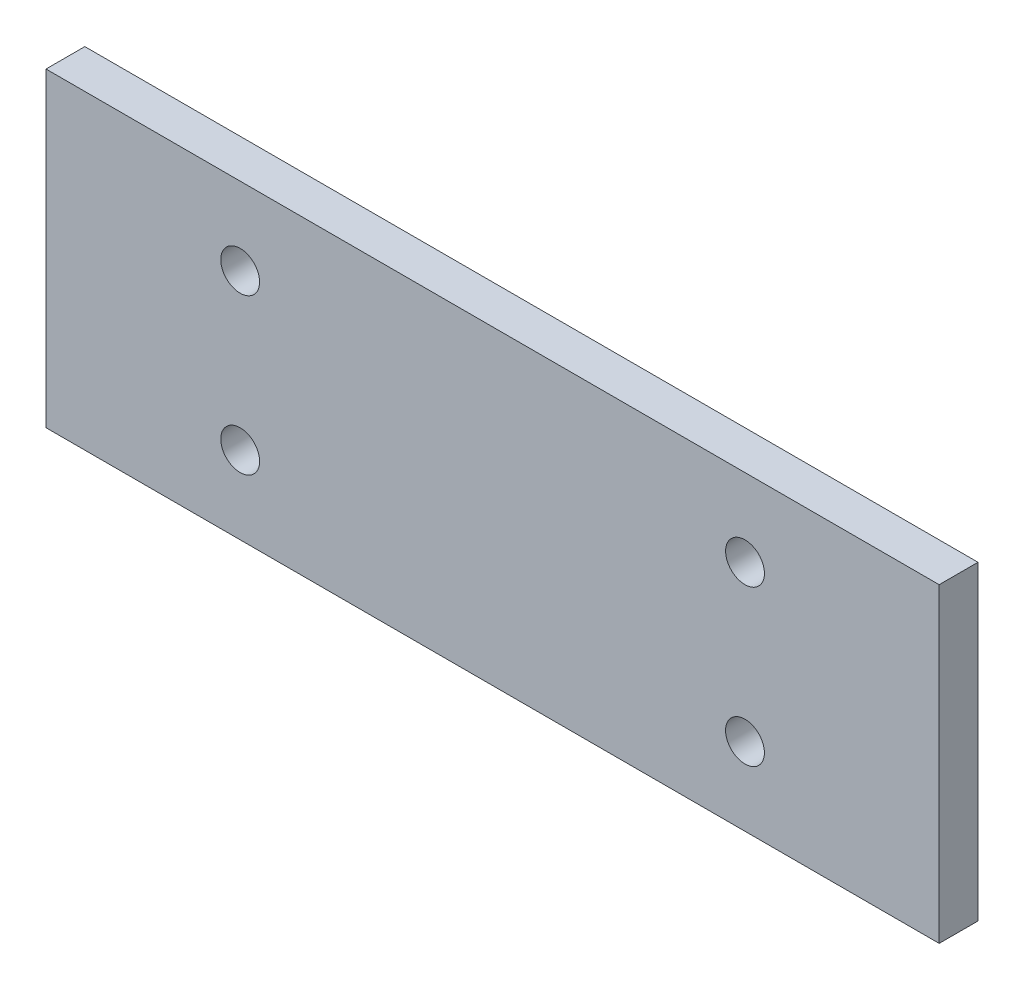
SolidWorks part; units mm, degrees
ref_plane "Front Plane" through (0, 0, 0) normal (0, 0, 1) x (1, 0, 0)
ref_plane "Top Plane" through (0, 0, 0) normal (0, 1, 0) x (1, 0, 0)
ref_plane "Right Plane" through (0, 0, 0) normal (1, 0, 0) x (0, 0, -1)
sketch "Sketch1" plane through (0, 0, 0) normal (0, 0, 1) x (1, 0, 0)
  line L0 (-12.1342, 0) -> (10.3507, 0) construction
  line L1 (-57.5, -20) -> (57.5, -20)
  line L2 (-57.5, -20) -> (-57.5, 20)
  line L3 (-57.5, 20) -> (57.5, 20)
  line L4 (57.5, -20) -> (57.5, 20)
  line L5 (-57.5, -20) -> (57.5, 20) construction
  line L6 (-57.5, 20) -> (57.5, -20) construction
  circle A0 centre (-32.5, 10) radius 2.5
  circle A1 centre (32.5, 10) radius 2.5
  circle A2 centre (32.5, -10) radius 2.5
  circle A3 centre (-32.5, -10) radius 2.5
  point P0 (0, 0)
  dimension "D4" = 5
  dimension "D5" = 5
  dimension "D1" = 115
  dimension "D2" = 25
  dimension "D3" = 65
  dimension "D6" = 10
  dimension "D7" = 40
  dimension "D8" = 20
extrude "Boss-Extrude1" add sketch "Sketch1" along normal blind 5
